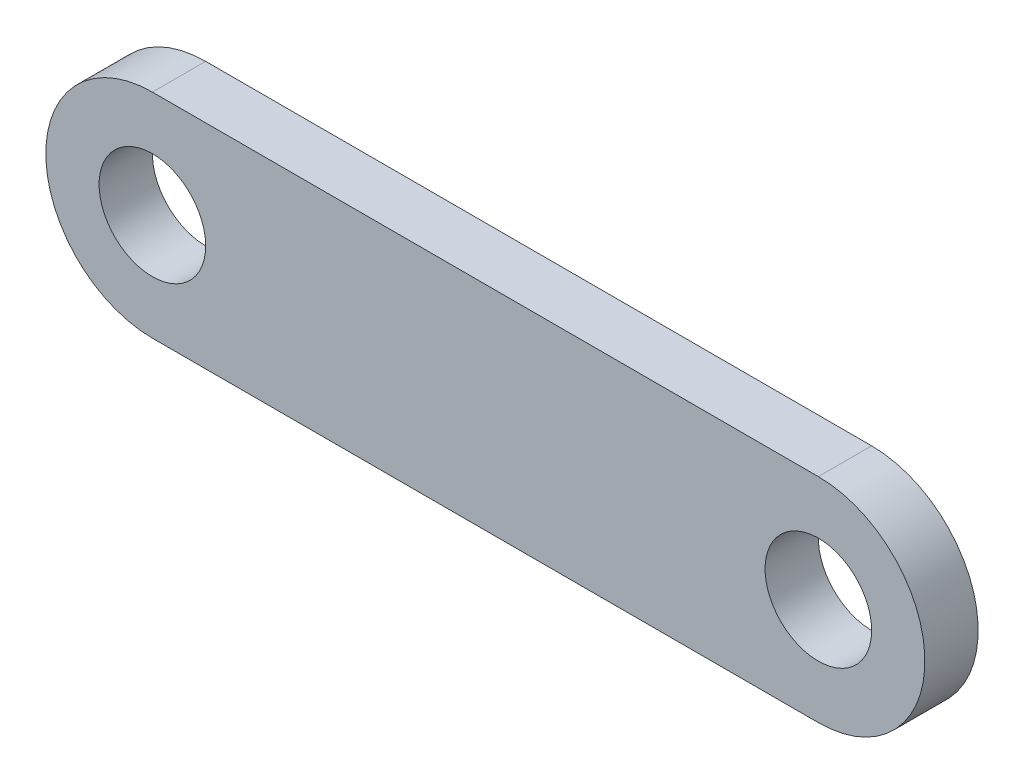
SolidWorks part; units mm, degrees
ref_plane "Front Plane" through (0, 0, 0) normal (0, 0, 1) x (1, 0, 0)
ref_plane "Top Plane" through (0, 0, 0) normal (0, 1, 0) x (1, 0, 0)
ref_plane "Right Plane" through (0, 0, 0) normal (1, 0, 0) x (0, 0, -1)
sketch "Sketch1" plane through (0, 0, 0) normal (0, 0, 1) x (1, 0, 0)
  line L0 (0, 0) -> (25, 0) construction
  line L1 (0, 4) -> (25, 4)
  line L2 (0, -4) -> (25, -4)
  arc A4 (0, 4) -> (0, -4) centre (0, 0) ccw
  arc A5 (25, -4) -> (25, 4) centre (25, 0) ccw
  circle A6 centre (0, 0) radius 2
  circle A7 centre (25, 0) radius 2
  point P2 (12.5, 0)
  dimension "D1" = 4
  dimension "D2" = 4
  dimension "D3" = 25
extrude "Boss-Extrude1" add sketch "Sketch1" along normal blind 2
